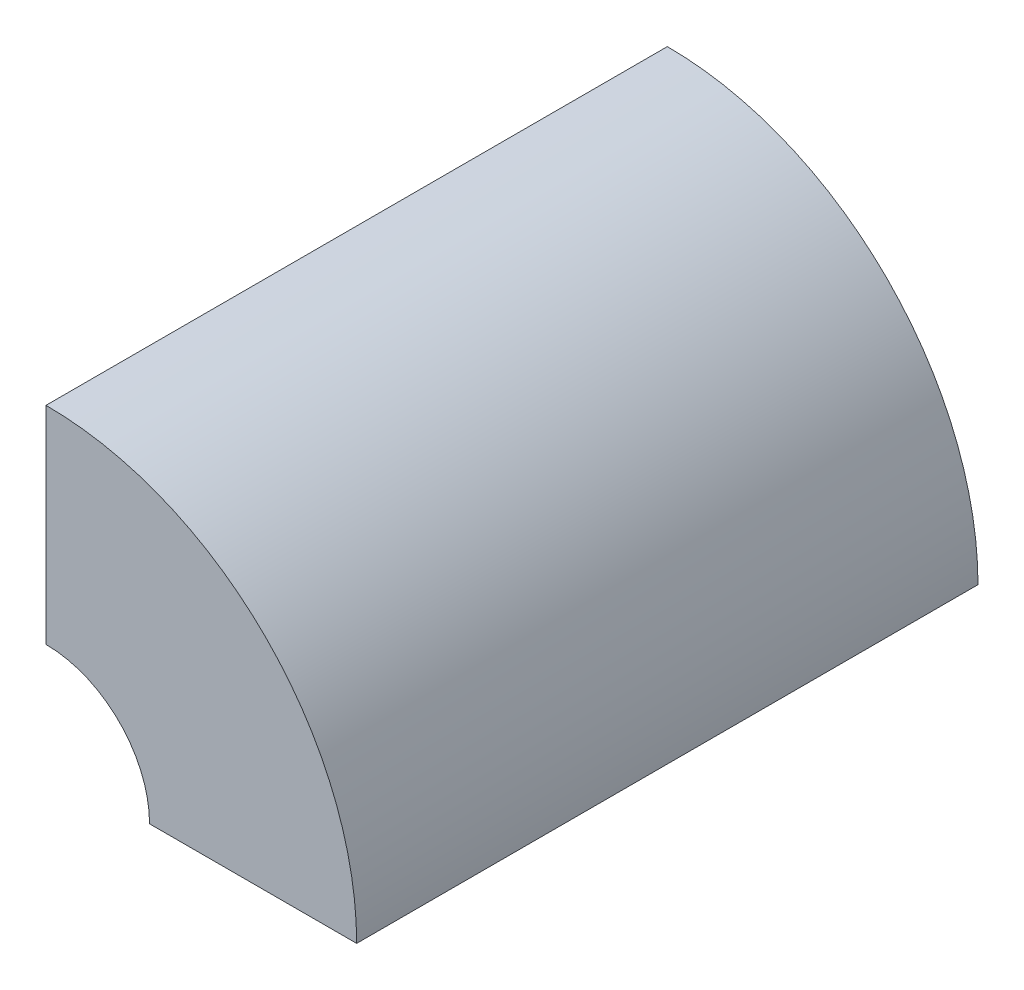
SolidWorks part; units mm, degrees
ref_plane "Front Plane" through (0, 0, 0) normal (0, 0, 1) x (1, 0, 0)
ref_plane "Top Plane" through (0, 0, 0) normal (0, 1, 0) x (1, 0, 0)
ref_plane "Right Plane" through (0, 0, 0) normal (1, 0, 0) x (0, 0, -1)
sketch "AnnulusProfile" plane through (0, 0, 0) normal (0, 1, 0) x (1, 0, 0)
  line L1 (2, 0) -> (6, 0)
  line L2 (2, 0) -> (2, -12)
  line L3 (2, -12) -> (6, -12)
  line L4 (6, 0) -> (6, -12)
  line L5 (0, 0) -> (0, -20) construction
  dimension "inner_radius_mm" = 2
  dimension "outer_radius_mm" = 6
  dimension "height_mm" = 12
revolve "Revolution" add sketch "AnnulusProfile" angle 90 about L5
